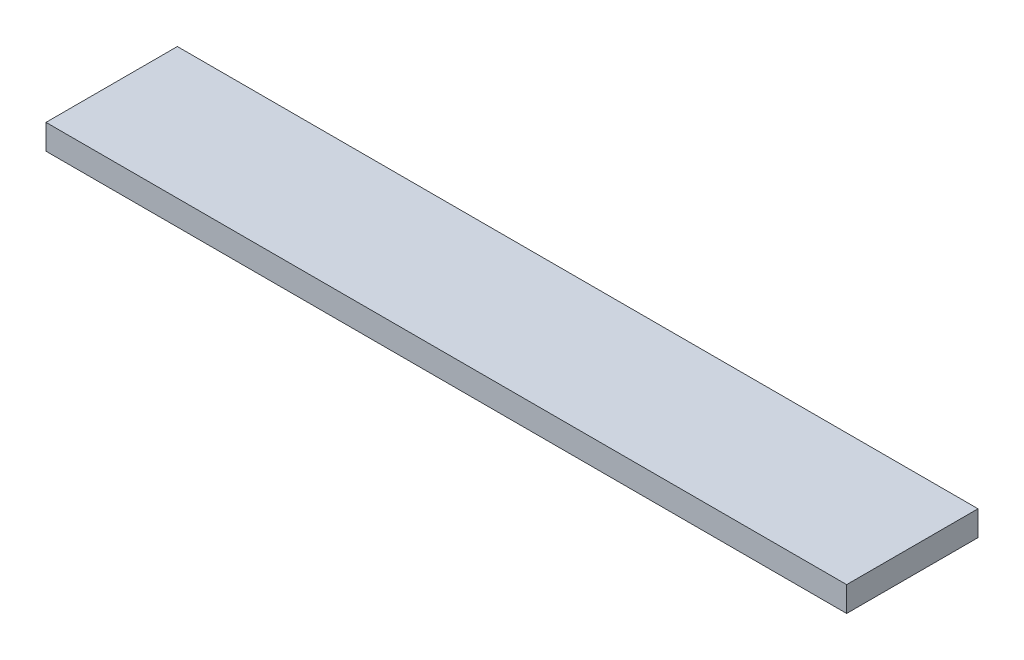
SolidWorks part; units mm, degrees
ref_plane "Front Plane" through (0, 0, 0) normal (0, 0, 1) x (1, 0, 0)
ref_plane "Top Plane" through (0, 0, 0) normal (0, 1, 0) x (1, 0, 0)
ref_plane "Right Plane" through (0, 0, 0) normal (1, 0, 0) x (0, 0, -1)
sketch "Sketch1" plane through (0, 0, 0) normal (0, 1, 0) x (1, 0, 0)
  line L1 (-64, -10.5) -> (64, -10.5)
  line L2 (-64, -10.5) -> (-64, 10.5)
  line L3 (-64, 10.5) -> (64, 10.5)
  line L4 (64, -10.5) -> (64, 10.5)
  line L5 (-64, -10.5) -> (64, 10.5) construction
  line L6 (-64, 10.5) -> (64, -10.5) construction
  point P0 (0, 0)
  dimension "D1" = 128
  dimension "D2" = 21
extrude "Boss-Extrude1" add sketch "Sketch1" along normal blind 4
